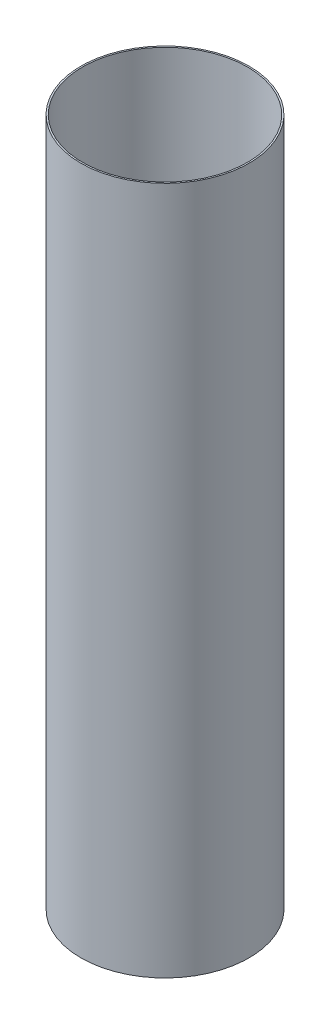
SolidWorks part; units mm, degrees
material "Thornel Mat VMA"
ref_plane "Front Plane" through (0, 0, 0) normal (0, 0, 1) x (1, 0, 0)
ref_plane "Top Plane" through (0, 0, 0) normal (0, 1, 0) x (1, 0, 0)
ref_plane "Right Plane" through (0, 0, 0) normal (1, 0, 0) x (0, 0, -1)
sketch "Sketch1" plane through (0, 0, 0) normal (0, 1, 0) x (1, 0, 0)
  circle A0 centre (0, 0) radius 77.6224
  circle A1 centre (0, 0) radius 76.2
  dimension "D1" = 155.2448
  dimension "D2" = 152.4
extrude "Boss-Extrude1" add sketch "Sketch1" along normal mid plane 635
equation "\"airframeInnerDiameter\"= 6in"
equation "\"outerDiameter\"= 6.112in"
equation "\"airframeBulkheadThickness\"= 0.125in"
equation "\"upperAirframeLength\"= 25in"
equation "\"D1@Sketch1\"=\"outerDiameter\""
equation "\"D2@Sketch1\"=\"airframeInnerDiameter\""
equation "\"D1@Boss-Extrude1\"=\"upperAirframeLength\""
